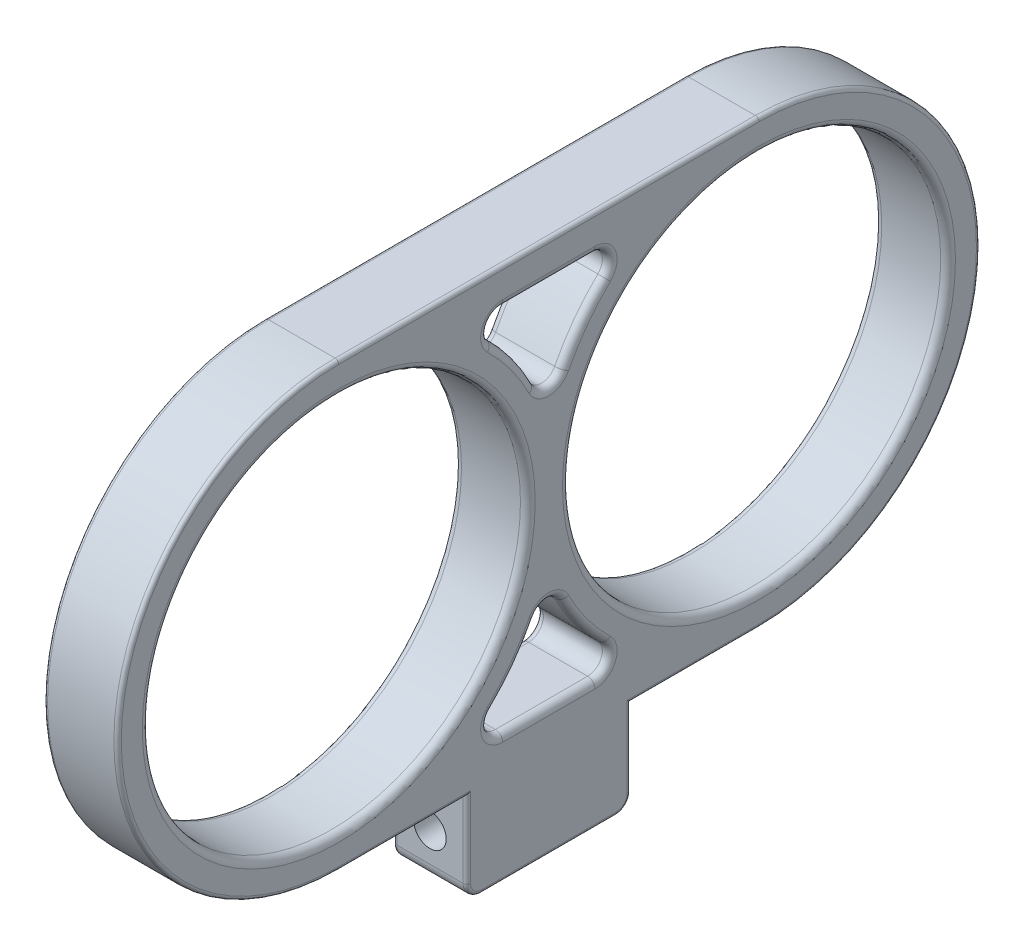
SolidWorks part; units mm, degrees
ref_plane "Front Plane" through (0, 0, 0) normal (0, 0, 1) x (1, 0, 0)
ref_plane "Top Plane" through (0, 0, 0) normal (0, 1, 0) x (1, 0, 0)
ref_plane "Right Plane" through (0, 0, 0) normal (1, 0, 0) x (0, 0, -1)
sketch "Sketch1" plane through (0, 0, 0) normal (1, 0, 0) x (0, 0, -1)
  line L0 (0, 0) -> (57, 0) construction
  line L1 (0, 30) -> (57, 30)
  line L2 (0, -30) -> (57, -30)
  line L3 (16.5831, 25) -> (40.4169, 25)
  line L4 (17.3748, -30) -> (39.6252, -30)
  line L5 (17.3748, -30) -> (17.3748, -42.3952)
  line L6 (17.3748, -42.3952) -> (39.6252, -42.3952)
  line L7 (39.6252, -30) -> (39.6252, -42.3952)
  line L8 (16.5831, -25) -> (40.4169, -25)
  circle A0 centre (0, 0) radius 25.65
  circle A1 centre (57, 0) radius 25.65
  arc A2 (0, 30) -> (0, -30) centre (0, 0) ccw
  arc A3 (57, -30) -> (57, 30) centre (57, 0) ccw
  arc A4 (28.5, 9.3675) -> (16.5831, 25) centre (0, 0) ccw
  arc A5 (28.5, 9.3675) -> (40.4169, 25) centre (57, 0) cw
  arc A6 (28.5, -9.3675) -> (16.5831, -25) centre (0, 0) cw
  arc A7 (28.5, -9.3675) -> (40.4169, -25) centre (57, 0) ccw
  point P5 (28.5, 0)
  point P15 (28.5, -42.3952)
  dimension "D1" = 51.3
  dimension "D3" = 30
  dimension "D7" = 30
  dimension "D2" = 57
  dimension "D4" = 22.2504
  dimension "D5" = 12.3952
  dimension "D6" = 5
extrude "Boss-Extrude1" add sketch "Sketch1" along normal blind 10
fillet "Fillet1" radius 2 2 edges at (5, -42.3952, -39.6252) (5, -42.3952, -17.3748)
fillet "Fillet4" radius 2 6 edges at (5, -25, -40.4169) (5, -9.3675, -28.5) (5, -25, -16.5831) (5, 9.3675, -28.5) (5, 25, -40.4169) (5, 25, -16.5831)
fillet "Fillet3" radius 1 28 edges at (10, 0, -82.65) (0, 0, -82.65) (0, 0, -25.65) (10, 0, -25.65) (0, 12.5516, -28.5) (0, 17.8446, -24.1158) (0, 23.75, -20.3945) (0, 25, -28.5) (0, 23.75, -36.6055) (0, -23.75, -20.3945) (0, -17.8446, -24.1158) (0, -12.5516, -28.5) (0, -17.8446, -32.8842) (0, -23.75, -36.6055) (10, 17.8446, -32.8842) (10, 23.75, -36.6055) (10, 25, -28.5) (10, 23.75, -20.3945) (10, 17.8446, -24.1158) (10, -12.5516, -28.5) (10, -17.8446, -32.8842) (10, -23.75, -36.6055) (10, -25, -28.5) (10, -23.75, -20.3945) (0, 17.8446, -32.8842) (0, -25, -28.5) (10, 12.5516, -28.5) (10, -17.8446, -24.1158)
fillet "Fillet2" radius 0.5 20 edges at (0, -30, -48.3126) (0, 0, -87) (0, 30, -28.5) (0, 0, 30) (0, -35.1976, -39.6252) (0, -41.8094, -39.0394) (0, -42.3952, -28.5) (0, -41.8094, -17.9606) (10, -35.1976, -17.3748) (10, -41.8094, -17.9606) (10, -35.1976, -39.6252) (10, -41.8094, -39.0394) (10, -30, -48.3126) (10, 0, -87) (10, 30, -28.5) (10, 0, 30) (0, -30, -8.6874) (0, -35.1976, -17.3748) (10, -42.3952, -28.5) (10, -30, -8.6874)
sketch "Sketch2" plane through (0, 0, -17.3748) normal (0, 0, 1) x (1, 0, 0)
  line L0 (9.5, -30) -> (0.5, -30) construction
  circle A0 centre (5, -36.35) radius 2.2
  point P4 (5, -30)
  dimension "D2" = 4.4
  dimension "D1" = 6.35
extrude "Cut-Extrude1" cut sketch "Sketch2" against normal up to next
